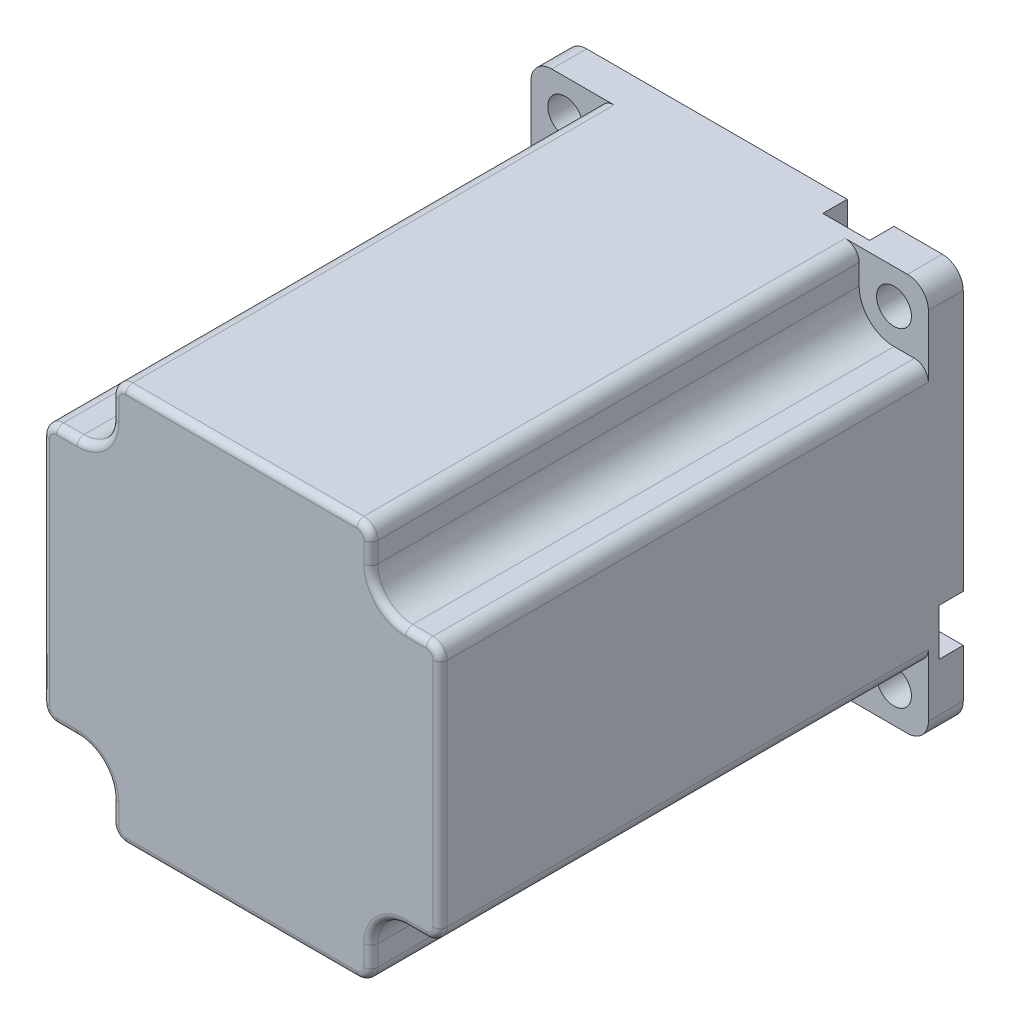
SolidWorks part; units mm, degrees
ref_plane "Front Plane" through (0, 0, 0) normal (0, 0, 1) x (1, 0, 0)
ref_plane "Top Plane" through (0, 0, 0) normal (0, 1, 0) x (1, 0, 0)
ref_plane "Right Plane" through (0, 0, 0) normal (1, 0, 0) x (0, 0, -1)
ref_plane "Plane1" through (0, 0, 0) normal (0, 0, -1) x (-1, 0, 0)
sketch "Sketch1" plane through (0, 0, 0) normal (0, 0, -1) x (-1, 0, 0)
  line L0 (-28.5, 28.5) -> (-28.5, -28.5141)
  line L1 (-28.5, -28.5141) -> (28.5, -28.497)
  line L2 (28.5, -28.497) -> (28.5, 28.5)
  line L3 (28.5, 28.5) -> (-28.5, 28.5)
extrude "Boss-Extrude1" add sketch "Sketch1" against normal blind 54
ref_plane "Plane2" through (-0.0086, -28.5056, 0) normal (-0.0003, -1, 0) x (1, -0.0003, 0)
ref_plane "Plane3" through (0, -18.57, 0) normal (0, 1, 0) x (1, 0, 0)
sketch "Sketch3" plane through (0, -18.57, 0) normal (0, 1, 0) x (1, 0, 0)
  line L0 (28.5, -5) -> (18.57, -5)
  line L1 (18.57, -5) -> (18.57, -54)
  line L2 (18.57, -54) -> (28.5, -54)
  line L3 (28.5, -54) -> (28.5, -5)
extrude "Cut-Extrude1" cut sketch "Sketch3" against normal up to surface up to plane "Plane2"
sketch "Sketch4" plane through (28.5, 0, 0) normal (1, 0, 0) x (0, 0, -1)
  line L0 (-5, 18.57) -> (-5, 28.5)
  line L1 (-5, 28.5) -> (-54, 28.5)
  line L2 (-54, 28.5) -> (-54, 18.57)
  line L3 (-54, 18.57) -> (-5, 18.57)
extrude "Cut-Extrude2" cut sketch "Sketch4" against normal blind 9.93
sketch "Sketch5" plane through (0, 28.5, 0) normal (0, 1, 0) x (-1, 0, 0)
  line L0 (18.57, 5) -> (28.5, 5)
  line L1 (28.5, 5) -> (28.5, 54)
  line L2 (28.5, 54) -> (18.57, 54)
  line L3 (18.57, 54) -> (18.57, 5)
extrude "Cut-Extrude3" cut sketch "Sketch5" against normal blind 9.93
sketch "Sketch7" plane through (0, -18.57, 0) normal (0, 1, 0) x (1, 0, 0)
  line L0 (-18.57, -5) -> (-28.5, -5)
  line L1 (-28.5, -5) -> (-28.5, -54)
  line L2 (-28.5, -54) -> (-18.57, -54)
  line L3 (-18.57, -54) -> (-18.57, -5)
extrude "Cut-Extrude4" cut sketch "Sketch7" against normal up to surface up to plane "Plane2"
sketch "Sketch8" plane through (0, 0, 0) normal (0, 0, -1) x (-1, 0, 0)
  line L0 (18.571, -28.5) -> (18.57, -25.149)
  line L1 (11.87, -25.1498) -> (11.8698, -28.502)
  line L2 (11.8698, -28.502) -> (18.571, -28.5)
  arc A0 (18.57, -25.149) -> (11.87, -25.1498) centre (15.22, -25.15) ccw
extrude "Cut-Extrude5" cut sketch "Sketch8" against normal blind 3.5
sketch "Sketch9" plane through (0, 0, 0) normal (0, 0, -1) x (-1, 0, 0)
  line L0 (-18.57, 28.5) -> (-18.57, 25.15)
  line L1 (-11.87, 25.15) -> (-11.87, 28.5)
  line L2 (-11.87, 28.5) -> (-18.57, 28.5)
  arc A0 (-18.57, 25.15) -> (-11.87, 25.15) centre (-15.22, 25.15) ccw
extrude "Cut-Extrude6" cut sketch "Sketch9" against normal blind 3.5
sketch "Sketch10" plane through (0, 0, 0) normal (0, 0, -1) x (-1, 0, 0)
  line L0 (-25.15, -11.87) -> (-28.5, -11.87)
  line L1 (-28.5, -11.87) -> (-28.5, -18.57)
  line L2 (-28.5, -18.57) -> (-25.15, -18.57)
  arc A0 (-25.15, -18.57) -> (-25.15, -11.87) centre (-25.15, -15.22) ccw
extrude "Cut-Extrude7" cut sketch "Sketch10" against normal blind 3.5
sketch "Sketch11" plane through (0, 0, 0) normal (0, 0, -1) x (-1, 0, 0)
  line L0 (28.5, 18.57) -> (25.15, 18.57)
  line L1 (25.15, 11.87) -> (28.5, 11.87)
  line L2 (28.5, 11.87) -> (28.5, 18.57)
  arc A0 (25.15, 18.57) -> (25.15, 11.87) centre (25.15, 15.22) ccw
extrude "Cut-Extrude8" cut sketch "Sketch11" against normal blind 3.5
draft "Draft1" type of draft neutral plane draft angle 0.017 faces to draft 1 face at (-5.0735, -28.5041, 11.25) neutral plane through (-18.571, -28.5, 3.5) neutral plane normal (1, -0.0003, 0) parameters "D1"=0.017
sketch "Sketch12" plane through (0, 0, 0) normal (0, 1, 0) x (1, 0, 0)
  line L0 (3.25, 24.6) -> (0, 24.6)
  line L1 (0, 24.6) -> (0, 0)
  line L2 (0, 0) -> (19.05, 0)
  line L3 (19.05, 0) -> (19.05, 1.6)
  line L4 (19.05, 1.6) -> (3.25, 1.6)
  line L5 (3.25, 1.6) -> (3.25, 24.6)
  line L6 (0, 24.6) -> (0, 0) construction
revolve "Revolve1" add sketch "Sketch12" angle 360 about L6
hole_wizard "Ø5.0 (5) Diameter Hole1" positions "Sketch14" profile "Sketch13" hole size "Ø5.0" standard "ANSI Metric"
sketch "Sketch14" plane through (0, 0, 5) normal (0, 0, 1) x (1, 0, 0)
  point P0 (23.57, -23.57)
  point P1 (23.57, 23.57)
  point P2 (-23.57, 23.57)
  point P3 (-23.57, -23.57)
sketch "Sketch13" plane through (23.57, -23.57, 5) normal (1, 0, 0) x (0, -1, 0)
  line L0 (0, 0) -> (0, 29.6)
  line L1 (0, 29.6) -> (2.5, 29.6)
  line L2 (2.5, 29.6) -> (2.5, 0)
  line L5 (2.5, 0) -> (0, 0)
  line L11 (0, -6.35) -> (0, 107.95) construction
  dimension "Thru Hole Dia." = 5
  dimension "Thru Hole Depth" = 29.6
hole_wizard "Ø5.0 (5) Diameter Hole2" positions "Sketch16" profile "Sketch15" hole size "Ø5.0" standard "ANSI Metric"
sketch "Sketch16" plane through (0, 0, 3.5) normal (0, 0, -1) x (-1, 0, 0)
  point P0 (15.22, -25.15)
  point P1 (-25.15, -15.22)
  point P2 (-15.22, 25.15)
  point P3 (25.15, 15.22)
sketch "Sketch15" plane through (-15.22, -25.15, 3.5) normal (1, 0, 0) x (0, 1, 0)
  line L0 (0, 0) -> (0, 26.5)
  line L1 (0, 26.5) -> (2.5, 26.5)
  line L2 (2.5, 26.5) -> (2.5, 0)
  line L5 (2.5, 0) -> (0, 0)
  line L10 (0, 26.5) -> (-2.5, 26.5) construction
  line L11 (0, -6.35) -> (0, 107.95) construction
  dimension "Hole Dia." = 5
  dimension "Hole Depth" = 26.5
  dimension "Drill Angle" = 180
fillet "Fillet1" radius 2 8 edges at (-28.5, 18.57, 29.5) (-18.57, -28.5, 29.5) (18.57, -28.5, 29.5) (28.5, -18.57, 29.5) (-18.57, 28.5, 29.5) (28.5, 18.57, 29.5) (18.57, 28.5, 29.5) (-28.5, -18.57, 29.5)
fillet "Fillet2" radius 5 4 edges at (18.57, -18.57, 29.5) (18.57, 18.57, 29.5) (-18.57, 18.57, 29.5) (-18.57, -18.57, 29.5)
fillet "Fillet3" radius 0.5 1 edges at (3.25, 0, -24.6)
fillet "Fillet5" radius 3 4 edges at (-28.5, -28.5, 2.5) (28.5, -28.5, 2.5) (-28.5, 28.5, 2.5) (28.5, 28.5, 2.5)
sketch "Sketch17" plane through (0, 0, 54) normal (0, 0, 1) x (1, 0, 0)
  line L0 (-16.57, 28.5) -> (16.57, 28.5)
  line L1 (18.57, 26.5) -> (18.57, 23.57)
  line L2 (23.57, 18.57) -> (26.5, 18.57)
  line L3 (28.5, 16.57) -> (28.5, -16.57) construction
  line L4 (28.5, 16.57) -> (28.5, -16.57)
  line L5 (26.5, -18.57) -> (23.57, -18.57)
  line L6 (18.57, -23.57) -> (18.57, -26.5)
  line L7 (16.57, -28.5) -> (-16.57, -28.5)
  line L8 (-18.57, -26.5) -> (-18.57, -23.57) construction
  line L9 (-18.57, -26.5) -> (-18.57, -23.57)
  line L11 (-23.57, -18.57) -> (-26.5, -18.57)
  line L12 (-28.5, -16.57) -> (-28.5, 16.57)
  line L13 (-26.5, 18.57) -> (-23.57, 18.57)
  line L14 (-18.57, 23.57) -> (-18.57, 26.5)
  arc A0 (16.57, 28.5) -> (18.57, 26.5) centre (16.57, 26.5) cw
  arc A1 (18.57, 23.57) -> (23.57, 18.57) centre (23.57, 23.57) ccw
  arc A2 (26.5, 18.57) -> (28.5, 16.57) centre (26.5, 16.57) cw
  arc A3 (28.5, -16.57) -> (26.5, -18.57) centre (26.5, -16.57) cw
  arc A4 (23.57, -18.57) -> (18.57, -23.57) centre (23.57, -23.57) ccw
  arc A5 (18.57, -26.5) -> (16.57, -28.5) centre (16.57, -26.5) cw
  arc A6 (-16.57, -28.5) -> (-18.57, -26.5) centre (-16.57, -26.5) cw
  arc A7 (-18.57, -26.5) -> (-16.57, -28.5) centre (-16.57, -26.5) ccw construction
  arc A8 (-18.57, -23.57) -> (-23.57, -18.57) centre (-23.57, -23.57) ccw
  arc A9 (-26.5, -18.57) -> (-28.5, -16.57) centre (-26.5, -16.57) cw
  arc A10 (-28.5, 16.57) -> (-26.5, 18.57) centre (-26.5, 16.57) cw
  arc A11 (-23.57, 18.57) -> (-18.57, 23.57) centre (-23.57, 23.57) ccw
  arc A12 (-18.57, 26.5) -> (-16.57, 28.5) centre (-16.57, 26.5) cw
extrude "Boss-Extrude2" add sketch "Sketch17" along normal blind 21
fillet "Fillet4" radius 1 24 edges at (-18.57, 25.035, 75) (-17.9842, 27.9142, 75) (-20.0345, 20.0345, 75) (-25.035, 18.57, 75) (-27.9142, 17.9842, 75) (-28.5, 0, 75) (-27.9142, -17.9842, 75) (-25.035, -18.57, 75) (-20.0345, -20.0345, 75) (-18.57, -25.035, 75) (-17.9842, -27.9142, 75) (0, -28.5, 75) (17.9842, -27.9142, 75) (18.57, -25.035, 75) (20.0345, -20.0345, 75) (25.035, -18.57, 75) (27.9142, -17.9842, 75) (28.5, 0, 75) (27.9142, 17.9842, 75) (25.035, 18.57, 75) (20.0345, 20.0345, 75) (18.57, 25.035, 75) (17.9842, 27.9142, 75) (0, 28.5, 75)
